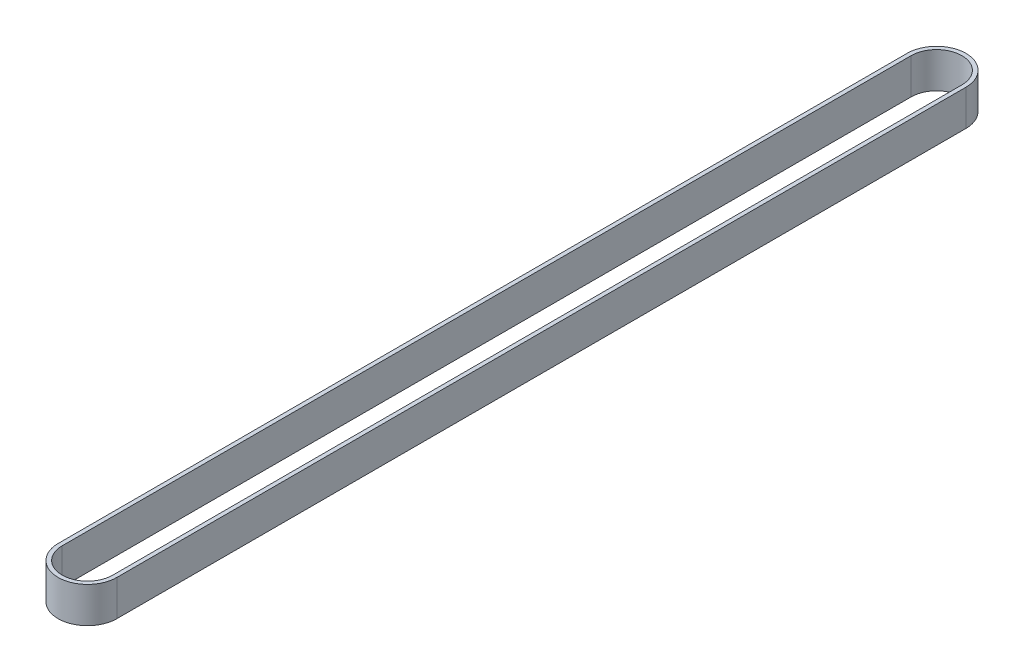
SolidWorks part; units mm, degrees
material "EPICHLOROHYDRIN"
ref_plane "前视基准面" through (0, 0, 0) normal (0, 0, 1) x (1, 0, 0)
ref_plane "上视基准面" through (0, 0, 0) normal (0, 1, 0) x (1, 0, 0)
ref_plane "右视基准面" through (0, 0, 0) normal (1, 0, 0) x (0, 0, -1)
sketch "草图1" plane through (0, 0, 0) normal (0, 1, 0) x (1, 0, 0)
  line L0 (0, 190) -> (0, -190) construction
  line L1 (11.35, 190) -> (11.35, -190)
  line L2 (-11.35, 190) -> (-11.35, -190)
  line L3 (0, 190) -> (0, -190) construction
  line L4 (13.15, 190) -> (13.15, -190)
  line L5 (-13.15, 190) -> (-13.15, -190)
  arc A0 (11.35, 190) -> (-11.35, 190) centre (0, 190) ccw
  arc A1 (-11.35, -190) -> (11.35, -190) centre (0, -190) ccw
  arc A2 (13.15, 190) -> (-13.15, 190) centre (0, 190) ccw
  arc A3 (-13.15, -190) -> (13.15, -190) centre (0, -190) ccw
  point P2 (0, 0)
  point P7 (0, 0)
  dimension "D2" = 11.35
  dimension "D4" = 0
  dimension "D5" = 13.15
  dimension "D1" = 0
  dimension "D3" = 380
extrude "凸台-拉伸1" add sketch "草图1" along normal mid plane 16
